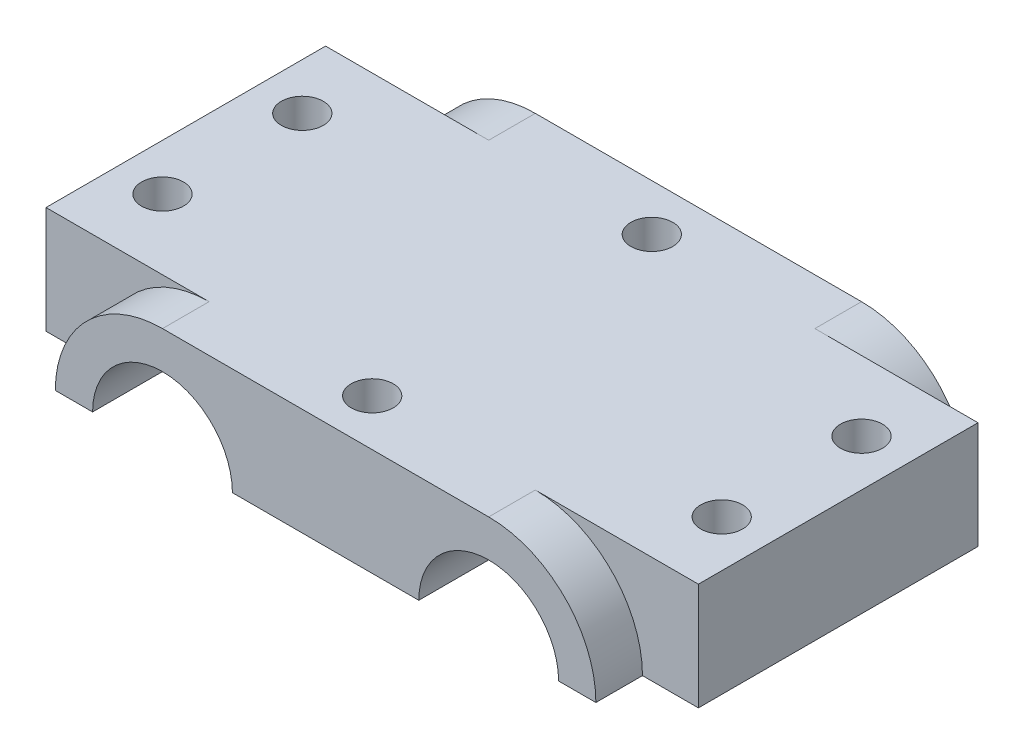
SolidWorks part; units mm, degrees
ref_plane "Front Plane" through (0, 0, 0) normal (0, 0, 1) x (1, 0, 0)
ref_plane "Top Plane" through (0, 0, 0) normal (0, 1, 0) x (1, 0, 0)
ref_plane "Right Plane" through (0, 0, 0) normal (1, 0, 0) x (0, 0, -1)
sketch "Sketch2" plane through (0, 0, 0) normal (0, 0, 1) x (1, 0, 0)
  line L1 (-35, 5.75) -> (35, 5.75)
  line L2 (-35, 5.75) -> (-35, -5.75)
  line L3 (-35, -5.75) -> (35, -5.75)
  line L4 (35, 5.75) -> (35, -5.75)
  line L5 (-35, 5.75) -> (35, -5.75) construction
  line L6 (-35, -5.75) -> (35, 5.75) construction
  point P0 (0, 0)
  dimension "D1" = 70
  dimension "D2" = 11.5
extrude "Boss-Extrude1" add sketch "Sketch2" along normal mid plane 40
sketch "Sketch3" plane through (0, 0, 20) normal (0, 0, 1) x (1, 0, 0)
  line L0 (-35, -5.75) -> (35, -5.75) construction
  line L1 (-25, -5.75) -> (-10, -5.75)
  line L2 (10, -5.75) -> (25, -5.75)
  line L3 (0, 0) -> (0, 14.569) construction
  arc A0 (10, -5.75) -> (25, -5.75) centre (17.5, -5.75) cw
  arc A1 (-10, -5.75) -> (-25, -5.75) centre (-17.5, -5.75) ccw
  dimension "D1" = 7.5
  dimension "D2" = 35
extrude "Cut-Extrude1" cut sketch "Sketch3" against normal blind 40
sketch "Sketch4" plane through (0, 0, 20) normal (0, 0, 1) x (1, 0, 0)
  line L0 (25, -5.75) -> (35, -5.75) construction
  line L1 (35, 5.75) -> (-35, 5.75) construction
  line L2 (35, -5.75) -> (35, 5.75) construction
  line L3 (-35, -5.75) -> (-25, -5.75) construction
  line L4 (-35, 5.75) -> (-35, -5.75) construction
  line L5 (-35, -5.75) -> (-29, -5.75)
  line L6 (-35, 5.75) -> (-35, -5.75)
  line L7 (35, 5.75) -> (17.5, 5.75)
  line L8 (35, -5.75) -> (35, 5.75)
  line L9 (29, -5.75) -> (35, -5.75)
  line L10 (0, 0) -> (0, -5.75) construction
  line L11 (-10, -5.75) -> (10, -5.75) construction
  line L12 (-17.5, 5.75) -> (-35, 5.75)
  arc A0 (29, -5.75) -> (17.5, 5.75) centre (17.5, -5.75) ccw
  arc A1 (-29, -5.75) -> (-17.5, 5.75) centre (-17.5, -5.75) cw
extrude "Cut-Extrude2" cut sketch "Sketch4" against normal blind 5
mirror "Mirror1" about plane through (0, 0, 0) normal (0, 0, 1) of "Cut-Extrude2"
hole_wizard "Ø1.0mm Dowel Hole1" positions "Sketch6" profile "Sketch7" hole size "Ø1.0" standard "ISO" end condition through all
sketch "Sketch6" plane through (0, 5.75, 0) normal (0, 1, 0) x (1, 0, 0)
  point P0 (30, -7.5)
  dimension "D1" = 30
  dimension "D2" = 7.5
sketch "Sketch7" plane through (30, 5.75, 7.5) normal (1, 0, 0) x (0, 0, 1)
  line L0 (0, 0) -> (0, 11.5)
  line L1 (0, 11.5) -> (2.25, 11.5)
  line L2 (2.25, 11.5) -> (2.25, 0)
  line L5 (2.25, 0) -> (0, 0)
  line L11 (0, -6.35) -> (0, 107.95) construction
  dimension "Thru Hole Dia." = 4.5
  dimension "Thru Hole Depth" = 11.5
pattern_linear "LPattern1" count 2 spacing 60 along (-1, 0, 0) count 2 spacing 15 along (0, 0, -1) of "Ø1.0mm Dowel Hole1"
hole_wizard "Ø1.0mm Dowel Hole2" positions "Sketch9" profile "Sketch10" hole size "Ø1.0" standard "ISO" end condition through all
sketch "Sketch9" plane through (0, 5.75, 0) normal (0, 1, 0) x (1, 0, 0)
  point P0 (0, -15)
  dimension "D1" = 15
sketch "Sketch10" plane through (0, 5.75, 15) normal (1, 0, 0) x (0, 0, 1)
  line L0 (0, 0) -> (0, 11.5)
  line L1 (0, 11.5) -> (2.25, 11.5)
  line L2 (2.25, 11.5) -> (2.25, 0)
  line L5 (2.25, 0) -> (0, 0)
  line L11 (0, -6.35) -> (0, 107.95) construction
  dimension "Thru Hole Dia." = 4.5
  dimension "Thru Hole Depth" = 11.5
mirror "Mirror2" about plane through (0, 0, 0) normal (0, 0, 1) of "Ø1.0mm Dowel Hole2"
